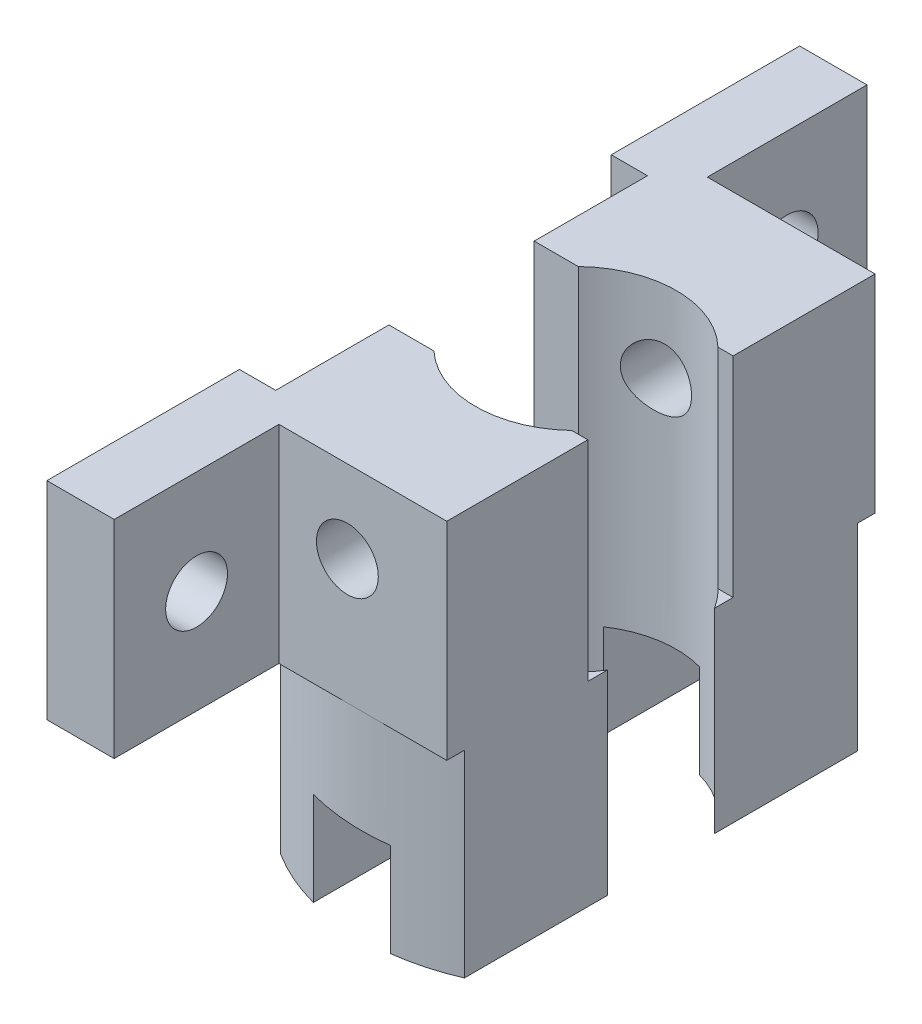
SolidWorks part; units mm, degrees
ref_plane "前基準面" through (0, 0, 0) normal (0, 0, 1) x (1, 0, 0)
ref_plane "上基準面" through (0, 0, 0) normal (0, 1, 0) x (1, 0, 0)
ref_plane "右基準面" through (0, 0, 0) normal (1, 0, 0) x (0, 0, -1)
sketch "草圖1" plane through (0, 0, 0) normal (0, 1, 0) x (1, 0, 0)
  circle A0 centre (0, 0) radius 9.68
  dimension "D1" = 19.36
extrude "伸長-薄件1" add sketch "草圖1" along normal blind 116.68 thin
ref_plane "平面1" through (-21, 0, 0) normal (1, 0, 0) x (0, 0, -1)
sketch "草圖11" plane through (0, 116.68, 0) normal (0, 1, 0) x (1, 0, 0)
  line L0 (-993.1634, -44.2358) -> (49006.8366, -44.2358) construction
  line L2 (35.2085, 30.7642) -> (8.2085, 30.7642)
  line L3 (35.2085, 30.7642) -> (35.2085, -119.2358)
  line L4 (35.2085, -119.2358) -> (8.2085, -119.2358)
  line L5 (8.2085, 30.7642) -> (8.2085, -119.2358)
  line L6 (35.2085, 30.7642) -> (8.2085, -119.2358) construction
  line L7 (35.2085, -119.2358) -> (8.2085, 30.7642) construction
  circle A0 centre (0, 0) radius 20.68 construction
  point P1 (21.7085, -44.2358)
  dimension "D1" = 150
  dimension "D2" = 27
  dimension "D3" = 30.7642
extrude "除料-伸長3" cut sketch "草圖11" against normal blind 40
ref_plane "平面2" through (0, 0, 21) normal (0, 0, 1) x (1, 0, 0)
sketch "草圖13" plane through (0, 0, 21) normal (0, 0, 1) x (1, 0, 0)
  line L0 (-21, -22.649) -> (-21, 22.649) construction
  line L1 (-21, 122.7847) -> (-11, 122.7847)
  line L2 (-21, 122.7847) -> (-21, -5.5603)
  line L3 (-21, -5.5603) -> (-11, -5.5603)
  line L4 (-11, 122.7847) -> (-11, -5.5603)
  dimension "D1" = 10
extrude "除料-伸長7" cut sketch "草圖13" against normal through all
sketch "草圖15" plane through (0, 0, 21) normal (0, 0, 1) x (1, 0, 0)
  line L0 (-1.3957, -883.32) -> (-1.3957, 49116.68) construction
  line L1 (8.2085, 116.68) -> (-11, 116.68) construction
  line L2 (-11, 0) -> (20.68, 0) construction
  line L3 (2.6043, 86.68) -> (-5.3957, 86.68)
  line L4 (2.6043, 86.68) -> (2.6043, 18)
  line L5 (2.6043, 18) -> (-5.3957, 18)
  line L6 (-5.3957, 86.68) -> (-5.3957, 18)
  line L7 (2.6043, 86.68) -> (-5.3957, 18) construction
  line L8 (2.6043, 18) -> (-5.3957, 86.68) construction
  point P1 (-1.3957, 52.34)
  point P5 (-1.3957, 116.68)
  dimension "D1" = 30
  dimension "D2" = 18
  dimension "D3" = 8
extrude "除料-伸長9" cut sketch "草圖15" against normal blind 48
sketch "草圖16" plane through (8.2085, 0, 0) normal (1, 0, 0) x (0, 0, -1)
  line L0 (20.68, 86.68) -> (20.68, 116.68) construction
  line L1 (5.1306, 116.68) -> (20.68, 116.68)
  line L2 (5.1306, 116.68) -> (5.1306, 96.68)
  line L3 (5.1306, 96.68) -> (20.68, 96.68)
  line L4 (20.68, 116.68) -> (20.68, 96.68)
  line L5 (-5.1306, 76.68) -> (-5.1306, 116.68) construction
  line L6 (-5.1306, 96.68) -> (-20.59, 96.68)
  line L7 (-5.1306, 96.68) -> (-5.1306, 116.68)
  line L8 (-5.1306, 116.68) -> (-20.59, 116.68)
  line L9 (-20.59, 96.68) -> (-20.59, 116.68)
  line L10 (-17.5118, 116.68) -> (-20.68, 116.68) construction
  dimension "D1" = 20
extrude "填料-伸長4" add sketch "草圖16" against normal blind 19.2
sketch "草圖17" plane through (0, 116.68, 0) normal (0, 1, 0) x (1, 0, 0)
  line L0 (-1009.59, 0) -> (48990.41, 0) construction
  line L1 (8.2085, 20.68) -> (8.2085, 5.1306) construction
  line L2 (8.2085, 6.97) -> (-11, 6.97)
  line L3 (8.2085, 6.97) -> (8.2085, -7.06)
  line L4 (8.2085, -7.06) -> (-11, -7.06)
  line L5 (-11, 6.97) -> (-11, -7.06)
  line L6 (-11, -17.5118) -> (-11, 17.5118) construction
  line L7 (-10.9915, -20.59) -> (-1.9273, -20.59) construction
  arc A0 (-8.2085, 5.1306) -> (-8.2085, -5.1306) centre (0, 0) ccw construction
  point P6 (-9.68, 0)
  dimension "D1" = 14.03
  dimension "D2" = 13.53
extrude "除料-伸長10" cut sketch "草圖17" against normal blind 20.2
sketch "草圖18" plane through (0, 0, 0) normal (0, -1, 0) x (1, 0, 0)
  circle A0 centre (0, 0) radius 9.59
extrude "除料-伸長11" cut sketch "草圖18" against normal through all
sketch "草圖21" plane through (0, 0, -20.68) normal (0, 0, -1) x (-1, 0, 0)
  line L0 (1.3915, 96.68) -> (1.3915, 105.73) construction
  line L1 (0, 96.68) -> (10.9915, 96.68) construction
  line L2 (1.3915, 105.73) -> (1.3915, 108.73) construction
  circle A0 centre (1.3915, 108.73) radius 2.985
  dimension "D3" = 5.97
  dimension "D1" = 9.05
  dimension "D2" = 3
extrude "除料-伸長12" cut sketch "草圖21" against normal blind 55.2
sketch "草圖23" plane through (0, 0, -20.68) normal (0, 0, -1) x (-1, 0, 0)
  line L0 (1.3915, 105.745) -> (1.3915, -11.785) construction
  circle A0 centre (1.3915, 108.73) radius 2.985 construction
  dimension "D1" = 117.53
sketch "草圖24" plane through (0, 0, 0) normal (0, -1, 0) x (1, 0, 0)
  circle A0 centre (0, 0) radius 9.59
extrude "伸長-薄件2" add sketch "草圖24" along normal blind 55.2 thin
sketch "草圖25" plane through (0, 0, 21) normal (0, 0, 1) x (1, 0, 0)
  line L0 (-1.3915, -11.785) -> (22.6124, -11.785)
  line L1 (22.6124, -11.785) -> (22.6124, -63.8733)
  line L2 (-22.7495, -63.8733) -> (22.6124, -63.8733)
  line L3 (-22.7495, -63.8733) -> (-22.7495, -11.785)
  line L4 (-22.7495, -11.785) -> (-1.3915, -11.785)
extrude "除料-伸長13" cut sketch "草圖25" against normal blind 55.2
sketch "草圖26" plane through (0, 0, 0) normal (0, 1, 0) x (1, 0, 0)
  line L0 (-21, -22.649) -> (-21, 22.649) construction
  line L1 (-10.9915, 20.68) -> (-21, 20.68)
  line L2 (-10.9915, 20.68) -> (-10.9915, -21)
  line L3 (-10.9915, -21) -> (-21, -21)
  line L4 (-21, 20.68) -> (-21, -21)
  line L5 (-17.6, -21) -> (17.6, -21) construction
extrude "除料-伸長15" cut sketch "草圖26" against normal blind 55.2
ref_plane "平面3" through (21, 0, 0) normal (1, 0, 0) x (0, 0, -1)
sketch "草圖27" plane through (21, 0, 0) normal (1, 0, 0) x (0, 0, -1)
  line L0 (0, -923.32) -> (0, 49076.68) construction
  line L1 (5.1306, 76.68) -> (-5.1306, 76.68) construction
  line L2 (18.9811, 76.68) -> (-18.9811, 76.68) construction
  line L3 (-5, 61.68) -> (5, 61.68)
  line L4 (-5, 61.68) -> (-5, 21.68)
  line L5 (-5, 21.68) -> (5, 21.68)
  line L6 (5, 61.68) -> (5, 21.68)
  line L7 (-5, 61.68) -> (5, 21.68) construction
  line L8 (-5, 21.68) -> (5, 61.68) construction
  point P1 (0, 41.68)
  point P5 (0, 76.68)
  dimension "D1" = 15
  dimension "D2" = 40
  dimension "D3" = 10
extrude "除料-伸長16" cut sketch "草圖27" against normal blind 55.2
sketch "草圖28" plane through (21, 0, 0) normal (1, 0, 0) x (0, 0, -1)
  line L1 (-22.4403, 4.804) -> (22.4403, 4.804)
  line L2 (-22.4403, 4.804) -> (-22.4403, -4.804)
  line L3 (-22.4403, -4.804) -> (22.4403, -4.804)
  line L4 (22.4403, 4.804) -> (22.4403, -4.804)
  line L5 (-22.4403, 4.804) -> (22.4403, -4.804) construction
  line L6 (-22.4403, -4.804) -> (22.4403, 4.804) construction
  point P0 (0, 0)
extrude "除料-伸長17" cut sketch "草圖28" against normal blind 12.2
sketch "草圖35" plane through (-10.9915, 0, 0) normal (-1, 0, 0) x (0, 0, 1)
  line L0 (20.59, 116.68) -> (20.59, 96.68)
  line L1 (20.59, 96.68) -> (7.06, 96.68)
  line L2 (7.06, 96.68) -> (7.06, 116.68)
  line L3 (7.06, 116.68) -> (20.59, 116.68)
extrude "填料-伸長10" add sketch "草圖35" along normal blind 15
sketch "草圖36" plane through (-10.9915, 0, 0) normal (-1, 0, 0) x (0, 0, 1)
  line L0 (-20.68, 116.68) -> (-6.97, 116.68)
  line L1 (-6.97, 116.68) -> (-6.97, 96.48)
  line L2 (-6.97, 96.48) -> (-20.68, 96.68)
  line L3 (-20.68, 96.68) -> (-20.68, 116.68)
extrude "填料-伸長11" add sketch "草圖36" along normal blind 15
sketch "草圖37" plane through (0, 0, 20.59) normal (0, 0, 1) x (1, 0, 0)
  line L0 (-25.9915, 96.68) -> (-1.9273, 96.68) construction
  line L1 (-25.9915, 116.68) -> (-16.9915, 116.68)
  line L2 (-25.9915, 116.68) -> (-25.9915, 96.68)
  line L3 (-25.9915, 96.68) -> (-16.9915, 96.68)
  line L4 (-16.9915, 116.68) -> (-16.9915, 96.68)
  dimension "D1" = 9
extrude "填料-伸長12" add sketch "草圖37" along normal blind 20
sketch "草圖38" plane through (0, 0, -20.68) normal (0, 0, -1) x (-1, 0, 0)
  line L0 (25.9915, 116.68) -> (-8.2085, 116.68) construction
  line L1 (25.9915, 96.68) -> (16.9915, 96.68)
  line L2 (25.9915, 96.68) -> (25.9915, 116.68)
  line L3 (25.9915, 116.68) -> (16.9915, 116.68)
  line L4 (16.9915, 96.68) -> (16.9915, 116.68)
  dimension "D1" = 9
extrude "填料-伸長13" add sketch "草圖38" along normal blind 20
sketch "草圖42" plane through (-16.9915, 0, 0) normal (1, 0, 0) x (0, 0, -1)
  line L0 (30.68, -903.32) -> (30.68, 49096.68) construction
  line L1 (40.68, 96.68) -> (20.68, 96.68) construction
  line L2 (-959.32, 106.68) -> (49040.68, 106.68) construction
  line L3 (40.68, 116.68) -> (40.68, 96.68) construction
  line L4 (-30.59, -903.32) -> (-30.59, 49096.68) construction
  line L5 (-40.59, 96.68) -> (-20.59, 96.68) construction
  circle A0 centre (30.68, 106.5544) radius 2.985
  circle A1 centre (-30.3956, 106.68) radius 2.985
  point P5 (30.68, 96.68)
  point P10 (40.68, 106.68)
  point P15 (-30.59, 96.68)
  dimension "D1" = 5.97
  dimension "D2" = 5.97
extrude "除料-伸長21" cut sketch "草圖42" against normal blind 20
sketch "草圖43" plane through (0, 116.68, 0) normal (0, 1, 0) x (1, 0, 0)
  line L0 (-11, 6.97) -> (-10.9915, 20.68)
  line L1 (-10.9915, 20.68) -> (-10.9915, 48.0968)
  line L2 (-10.9915, 48.0968) -> (-28.2748, 48.0968)
  line L3 (-28.2748, 48.0968) -> (-28.2748, -43.2705)
  line L4 (-28.2748, -43.2705) -> (-11, -43.2705)
  line L5 (-11, -43.2705) -> (-11, 6.97)
extrude "除料-伸長23" cut sketch "草圖43" against normal through all
sketch "草圖45" plane through (0, 0, 20.59) normal (0, 0, 1) x (1, 0, 0)
  line L0 (-11, 96.68) -> (-1.9273, 96.68) construction
  line L1 (-11, 116.68) -> (-8, 116.68)
  line L2 (-11, 116.68) -> (-11, 96.68)
  line L3 (-11, 96.68) -> (-8, 96.68)
  line L4 (-8, 116.68) -> (-8, 96.68)
  dimension "D1" = 3
extrude "填料-伸長14" add sketch "草圖45" along normal blind 30
sketch "草圖46" plane through (0, 0, -20.68) normal (0, 0, -1) x (-1, 0, 0)
  line L0 (0, 96.68) -> (10.9915, 96.68) construction
  line L1 (10.9915, 116.68) -> (7.9915, 116.68)
  line L2 (10.9915, 116.68) -> (10.9915, 96.68)
  line L3 (10.9915, 96.68) -> (7.9915, 96.68)
  line L4 (7.9915, 116.68) -> (7.9915, 96.68)
  dimension "D1" = 3
extrude "填料-伸長15" add sketch "草圖46" along normal blind 30
sketch "草圖47" plane through (-11, 0, 0) normal (-1, 0, 0) x (0, 0, 1)
  line L0 (50.59, 116.68) -> (7.06, 116.68) construction
  line L1 (50.59, 96.68) -> (17.5118, 96.68)
  line L2 (50.59, 96.68) -> (50.59, 116.68)
  line L3 (50.59, 116.68) -> (17.5118, 116.68)
  line L4 (17.5118, 96.68) -> (17.5118, 116.68)
extrude "填料-伸長16" add sketch "草圖47" along normal blind 50
sketch "草圖48" plane through (-10.9915, 0, 0) normal (-1, 0, 0) x (0, 0, 1)
  line L1 (-50.68, 116.68) -> (-20.68, 116.68)
  line L2 (-50.68, 116.68) -> (-50.68, 96.68)
  line L3 (-50.68, 96.68) -> (-20.68, 96.68)
  line L4 (-20.68, 116.68) -> (-20.68, 96.68)
extrude "填料-伸長17" add sketch "草圖48" along normal blind 50
sketch "草圖50" plane through (0, 0, 17.5118) normal (0, 0, -1) x (-1, 0, 0)
  line L0 (11, 96.68) -> (11, 116.68)
  line L1 (11, 116.68) -> (61, 116.68)
  line L2 (61, 116.68) -> (61, 96.68)
  line L3 (61, 96.68) -> (11, 96.68)
extrude "填料-伸長18" add sketch "草圖50" along normal blind 1
sketch "草圖51" plane through (0, 0, -20.68) normal (0, 0, 1) x (1, 0, 0)
  line L0 (-10.9915, 116.68) -> (-10.9915, 96.68)
  line L1 (-10.9915, 96.68) -> (-60.9915, 96.68)
  line L2 (-60.9915, 96.68) -> (-60.9915, 116.68)
  line L3 (-60.9915, 116.68) -> (-10.9915, 116.68)
extrude "填料-伸長19" add sketch "草圖51" along normal blind 1
sketch "草圖52" plane through (0, 116.68, 0) normal (0, 1, 0) x (1, 0, 0)
  line L0 (-34.4915, -949.32) -> (-34.4915, 49050.68) construction
  line L1 (-60.9915, 50.68) -> (-7.9915, 50.68) construction
  line L2 (-1007.9915, 35.68) -> (48992.0085, 35.68) construction
  line L3 (-7.9915, 50.68) -> (-7.9915, 20.68) construction
  line L4 (-60.9915, 19.68) -> (-60.9915, 50.68) construction
  line L5 (-7.9915, 50.68) -> (-60.9915, 50.68)
  line L6 (-7.9915, 50.68) -> (-7.9915, 36.68)
  line L7 (-7.9915, 36.68) -> (-60.9915, 36.68)
  line L8 (-60.9915, 50.68) -> (-60.9915, 36.68)
  point P5 (-34.4915, 50.68)
  point P10 (-7.9915, 35.68)
  dimension "D1" = 14
extrude "除料-伸長24" cut sketch "草圖52" against normal through all
sketch "草圖53" plane through (0, 116.68, 0) normal (0, 1, 0) x (1, 0, 0)
  line L0 (-61, -50.59) -> (-61, -16.5118) construction
  line L1 (-8, -50.59) -> (-61, -50.59)
  line L2 (-8, -50.59) -> (-8, -36.59)
  line L3 (-8, -36.59) -> (-61, -36.59)
  line L4 (-61, -50.59) -> (-61, -36.59)
  dimension "D1" = 14
extrude "除料-伸長25" cut sketch "草圖53" against normal through all
sketch "草圖54" plane through (0, 116.68, 0) normal (0, 1, 0) x (1, 0, 0)
  line L0 (-60.9915, 36.68) -> (-7.9915, 36.68) construction
  line L1 (-61, -36.59) -> (-21, -36.59)
  line L2 (-61, -36.59) -> (-61, 36.68)
  line L3 (-61, 36.68) -> (-21, 36.68)
  line L4 (-21, -36.59) -> (-21, 36.68)
  dimension "D1" = 40
extrude "除料-伸長26" cut sketch "草圖54" against normal through all
sketch "草圖55" plane through (0, 116.68, 0) normal (0, 1, 0) x (1, 0, 0)
  line L0 (-15.0276, -36.59) -> (-15.0276, -16.5118) construction
  line L1 (-8, -36.59) -> (-21, -36.59) construction
  line L2 (-21, -16.5118) -> (-11, -16.5118) construction
  line L3 (-13.4574, 19.68) -> (-13.4574, 39.76) construction
  line L4 (-10.9921, 19.68) -> (-21, 19.68) construction
  dimension "D1" = 20.08
sketch "草圖56" plane through (0, 0, -36.68) normal (0, 0, -1) x (-1, 0, 0)
  line L1 (7.9915, 96.68) -> (21, 96.68)
  line L2 (7.9915, 96.68) -> (7.9915, 116.68)
  line L3 (7.9915, 116.68) -> (21, 116.68)
  line L4 (21, 96.68) -> (21, 116.68)
extrude "填料-伸長21" add sketch "草圖56" along normal blind 3.08
ref_plane "平面4" through (0, 0, 50) normal (0, 0, 1) x (1, 0, 0)
sketch "草圖58" plane through (0, 0, 50) normal (0, 0, 1) x (1, 0, 0)
  line L1 (-22.571, -18.3082) -> (22.1011, -18.3082)
  line L2 (-22.571, -18.3082) -> (-22.571, 77.6317)
  line L3 (-22.571, 77.6317) -> (22.1011, 77.6317)
  line L4 (22.1011, -18.3082) -> (22.1011, 77.6317)
extrude "除料-伸長28" cut sketch "草圖58" against normal through all
sketch "草圖59" plane through (0, 77.6317, 0) normal (0, -1, 0) x (1, 0, 0)
  circle A0 centre (0, 0) radius 9.7
  dimension "D1" = 19.4
extrude "除料-伸長29" cut sketch "草圖59" against normal through all
sketch "草圖60" plane through (0, 116.68, 0) normal (0, 1, 0) x (1, 0, 0)
  line L0 (-21, 39.76) -> (-7.9915, 39.76) construction
  line L1 (-21, -36.59) -> (-14.4957, -36.59)
  line L2 (-21, -36.59) -> (-21, 39.76)
  line L3 (-21, 39.76) -> (-14.4957, 39.76)
  line L4 (-14.4957, -36.59) -> (-14.4957, 39.76)
extrude "除料-伸長30" cut sketch "草圖60" against normal through all
sketch "草圖61" plane through (0, 116.68, 0) normal (0, 1, 0) x (1, 0, 0)
  line L0 (1.9273, -20.59) -> (1.9273, -22.3991)
  line L1 (1.9273, -22.3991) -> (-2.1742, -21.4215)
  line L2 (-2.1742, -21.4215) -> (-2.1742, -20.59)
  line L3 (-8, -20.59) -> (-1.9273, -20.59) construction
  line L4 (-2.1742, -20.59) -> (1.9273, -20.59)
extrude "除料-伸長32" cut sketch "草圖61" against normal blind 20
sketch "草圖64" plane through (0, 116.68, 0) normal (0, 1, 0) x (1, 0, 0)
  line L1 (-8, -20.59) -> (8.2085, -20.59)
  line L2 (-8, -20.59) -> (-8, -20.68)
  line L3 (-8, -20.68) -> (8.2085, -20.68)
  line L4 (8.2085, -20.59) -> (8.2085, -20.68)
  dimension "D1" = 0.09
extrude "填料-伸長22" add sketch "草圖64" against normal blind 20
sketch "草圖65" plane through (0, 116.68, 0) normal (0, 1, 0) x (1, 0, 0)
  line L0 (-11, 6.97) -> (-10.9921, 19.68) construction
  line L1 (-11, -7.06) -> (-11, -16.5118) construction
  line L2 (-14.4957, -36.59) -> (-14.4957, -16.5118) construction
  line L3 (-11, -16.5118) -> (-14.4957, -16.5118)
  line L4 (-11, -16.5118) -> (-11, -19.7718)
  line L5 (-11, -19.7718) -> (-14.4957, -19.7718)
  line L6 (-14.4957, -16.5118) -> (-14.4957, -19.7718)
  dimension "D1" = 12.71
  dimension "D2" = 9.4518
  dimension "D3" = 3.26
extrude "除料-伸長33" cut sketch "草圖65" against normal through all
sketch "草圖66" plane through (0, 96.48, 0) normal (0, 1, 0) x (1, 0, 0)
  line L0 (-1011, -0.045) -> (48989, -0.045) construction
  line L1 (-11, 6.97) -> (-11, -7.06) construction
  line L2 (-12.9194, -0.045) -> (-12.9194, 17.905) construction
  line L3 (-12.9194, -0.045) -> (-12.9194, -17.995) construction
  line L4 (-11, -19.7718) -> (-11, -7.06) construction
  line L5 (-14.4957, -19.7718) -> (-11, -19.7718)
  line L6 (-14.4957, -19.7718) -> (-14.4957, -17.995)
  line L7 (-14.4957, -17.995) -> (-11, -17.995)
  line L8 (-11, -19.7718) -> (-11, -17.995)
  line L10 (-10.9921, 19.68) -> (-14.4957, 19.68)
  line L11 (-10.9921, 19.68) -> (-10.9921, 17.905)
  line L12 (-10.9921, 17.905) -> (-14.4957, 17.905)
  line L13 (-14.4957, 19.68) -> (-14.4957, 17.905)
  point P5 (-11, -0.045)
  dimension "D1" = 17.95
  dimension "D2" = 17.95
extrude "填料-伸長23" add sketch "草圖66" along normal blind 20.2
sketch "草圖68" plane through (0, 116.68, 0) normal (0, 1, 0) x (1, 0, 0)
  line L0 (-10.9932, 17.905) -> (-10.9932, 39.76) construction
  line L1 (-14.4957, 39.76) -> (-7.9915, 39.76) construction
  line L2 (-14.4957, 17.905) -> (-14.4957, 39.76) construction
  line L3 (-7.9915, 39.76) -> (-14.4957, 39.76)
  line L4 (-7.9915, 39.76) -> (-7.9915, 36.1)
  line L5 (-7.9915, 36.1) -> (-14.4957, 36.1)
  line L6 (-14.4957, 39.76) -> (-14.4957, 36.1)
  dimension "D1" = 3.66
extrude "除料-伸長34" cut sketch "草圖68" against normal blind 20
sketch "草圖69" plane through (-7.9915, 0, 0) normal (1, 0, 0) x (0, 0, -1)
  line L0 (28.39, -903.32) -> (28.39, 49096.68) construction
  line L1 (36.1, 96.68) -> (20.68, 96.68) construction
  line L2 (-28.635, -903.32) -> (-28.635, 49096.68) construction
  line L3 (-36.59, 96.68) -> (-20.68, 96.68) construction
  line L4 (-963.9, 106.68) -> (49036.1, 106.68) construction
  line L5 (36.1, 96.68) -> (36.1, 116.68) construction
  circle A0 centre (28.39, 106.68) radius 2.985
  circle A1 centre (-28.635, 106.68) radius 2.985
  point P5 (28.39, 96.68)
  point P10 (-28.635, 96.68)
  point P15 (36.1, 106.68)
  dimension "D1" = 5.97
  dimension "D2" = 5.97
extrude "除料-伸長35" cut sketch "草圖69" against normal through all
sketch "草圖70" plane through (0, 0, 20.59) normal (0, 0, -1) x (-1, 0, 0)
  circle A0 centre (1.3915, 108.73) radius 2.985
  dimension "D1" = 5.97
extrude "除料-伸長36" cut sketch "草圖70" against normal through all
sketch "草圖71" plane through (0, 116.68, 0) normal (0, 1, 0) x (1, 0, 0)
  line L0 (-7.9915, 20.68) -> (-7.9915, 6.97) construction
  line L1 (-6.746, 6.97) -> (-11, 6.97) construction
  line L2 (-9.7, 0) -> (-11, 0) construction
  line L3 (-11, 6.97) -> (-11, -17.5118) construction
  arc A0 (-5.3957, 8.0608) -> (-5.3957, -8.0608) centre (0, 0) ccw construction
  dimension "D1" = 1.3
